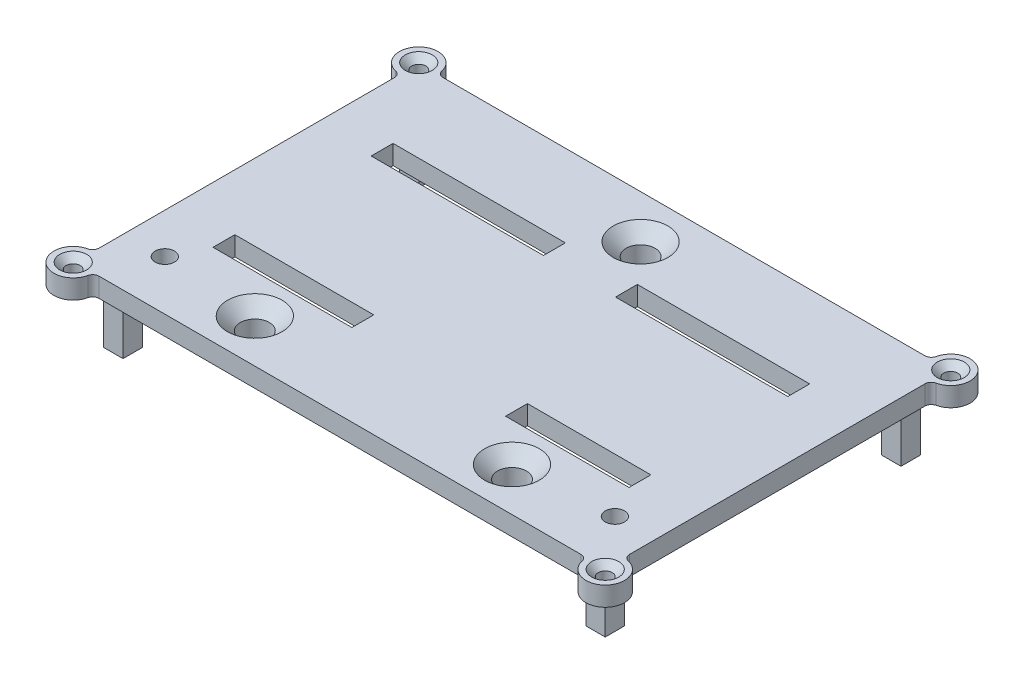
SolidWorks part; units mm, degrees
ref_plane "前视基准面" through (0, 0, 0) normal (0, 0, 1) x (1, 0, 0)
ref_plane "上视基准面" through (0, 0, 0) normal (0, 1, 0) x (1, 0, 0)
ref_plane "右视基准面" through (0, 0, 0) normal (1, 0, 0) x (0, 0, -1)
sketch "草图1" plane through (0, 0, 0) normal (0, 1, 0) x (1, 0, 0)
  line L0 (37.469, -26.75) -> (-37.469, -26.75)
  line L1 (41.25, -10.5) -> (41.25, -22.969)
  line L2 (41.25, -10.5) -> (39.25, -10.5)
  line L3 (39.25, -10.5) -> (39.25, -24.75)
  line L4 (39.25, -24.75) -> (-39.25, -24.75)
  line L5 (-39.25, -24.75) -> (-39.25, 24.75)
  line L6 (-39.25, 24.75) -> (39.25, 24.75)
  line L7 (39.25, 24.75) -> (39.25, 10.5)
  line L8 (41.25, 10.5) -> (39.25, 10.5)
  line L9 (41.25, 22.969) -> (41.25, 10.5)
  line L10 (-37.469, 26.75) -> (37.469, 26.75)
  line L11 (-41.25, -22.969) -> (-41.25, 22.969)
  circle A0 centre (41.3713, 26.8713) radius 0.85
  circle A1 centre (41.3713, -26.8713) radius 0.85
  circle A2 centre (-41.3713, -26.8713) radius 0.85
  circle A3 centre (-41.3713, 26.8713) radius 0.85
  arc A4 (38.4446, -27.5303) -> (37.469, -26.75) centre (37.469, -27.75) ccw
  arc A5 (38.4446, -27.5303) -> (42.0303, -23.9446) centre (41.3713, -26.8713) ccw
  arc A6 (41.25, -22.969) -> (42.0303, -23.9446) centre (42.25, -22.969) ccw
  arc A7 (42.0303, 23.9446) -> (41.25, 22.969) centre (42.25, 22.969) ccw
  arc A8 (42.0303, 23.9446) -> (38.4446, 27.5303) centre (41.3713, 26.8713) ccw
  arc A9 (37.469, 26.75) -> (38.4446, 27.5303) centre (37.469, 27.75) ccw
  arc A10 (-38.4446, 27.5303) -> (-37.469, 26.75) centre (-37.469, 27.75) ccw
  arc A11 (-38.4446, 27.5303) -> (-42.0303, 23.9446) centre (-41.3713, 26.8713) ccw
  arc A12 (-41.25, 22.969) -> (-42.0303, 23.9446) centre (-42.25, 22.969) ccw
  arc A13 (-42.0303, -23.9446) -> (-41.25, -22.969) centre (-42.25, -22.969) ccw
  arc A14 (-42.0303, -23.9446) -> (-38.4446, -27.5303) centre (-41.3713, -26.8713) ccw
  arc A15 (-37.469, -26.75) -> (-38.4446, -27.5303) centre (-37.469, -27.75) ccw
sketch "草图2" plane through (0, 0, 0) normal (0, 1, 0) x (1, 0, 0)
  line L0 (37.469, -26.75) -> (-37.469, -26.75) construction
  line L1 (-41.25, -22.969) -> (-41.25, 22.969) construction
  line L2 (-37.469, 26.75) -> (37.469, 26.75) construction
  line L3 (37.469, -26.75) -> (-37.469, -26.75)
  line L4 (-41.25, -22.969) -> (-41.25, 22.969)
  line L5 (-37.469, 26.75) -> (37.469, 26.75)
  line L6 (41.25, 22.969) -> (41.25, -22.969)
  line L8 (-32, 24.75) -> (-32, -24.75) construction
  line L9 (-39.25, 24.75) -> (39.25, 24.75) construction
  line L10 (39.25, -24.75) -> (-39.25, -24.75) construction
  line L11 (-39.25, -24.75) -> (-39.25, 24.75) construction
  line L12 (-39.25, 13.5) -> (39.25, 13.5) construction
  line L13 (39.25, 24.75) -> (39.25, 10.5) construction
  line L14 (-39.25, -13.5) -> (39.25, -13.5) construction
  line L15 (39.25, -10.5) -> (39.25, -24.75) construction
  line L16 (0, 24.75) -> (0, 20) construction
  line L17 (-32, 13.5) -> (-6.2, 13.5)
  line L18 (-32, 13.5) -> (-32, 11.1)
  line L19 (-32, 11.1) -> (-6.2, 11.1)
  line L20 (-6.2, 13.5) -> (-6.2, 11.1)
  line L21 (6, 13.5) -> (31.8, 13.5)
  line L22 (6, 13.5) -> (6, 11.1)
  line L23 (6, 11.1) -> (31.8, 11.1)
  line L24 (31.8, 13.5) -> (31.8, 11.1)
  line L25 (-32, -13.5) -> (-11.4, -13.5)
  line L26 (-32, -13.5) -> (-32, -11.1)
  line L27 (-32, -11.1) -> (-11.4, -11.1)
  line L28 (-11.4, -13.5) -> (-11.4, -11.1)
  line L29 (13.5, -13.5) -> (31.7, -13.5)
  line L30 (13.5, -13.5) -> (13.5, -11.1)
  line L31 (13.5, -11.1) -> (31.7, -11.1)
  line L32 (31.7, -13.5) -> (31.7, -11.1)
  line L33 (0, -24.75) -> (0, -20) construction
  line L34 (-20, -20) -> (20, -20) construction
  arc A0 (41.25, -22.969) -> (42.0303, -23.9446) centre (42.25, -22.969) ccw construction
  arc A1 (38.4446, -27.5303) -> (42.0303, -23.9446) centre (41.3713, -26.8713) ccw construction
  arc A2 (38.4446, -27.5303) -> (37.469, -26.75) centre (37.469, -27.75) ccw construction
  arc A3 (-37.469, -26.75) -> (-38.4446, -27.5303) centre (-37.469, -27.75) ccw construction
  arc A4 (-42.0303, -23.9446) -> (-38.4446, -27.5303) centre (-41.3713, -26.8713) ccw construction
  arc A5 (-42.0303, -23.9446) -> (-41.25, -22.969) centre (-42.25, -22.969) ccw construction
  arc A6 (-41.25, 22.969) -> (-42.0303, 23.9446) centre (-42.25, 22.969) ccw construction
  arc A7 (-38.4446, 27.5303) -> (-37.469, 26.75) centre (-37.469, 27.75) ccw construction
  arc A8 (-38.4446, 27.5303) -> (-42.0303, 23.9446) centre (-41.3713, 26.8713) ccw construction
  arc A9 (42.0303, 23.9446) -> (41.25, 22.969) centre (42.25, 22.969) ccw construction
  arc A10 (42.0303, 23.9446) -> (38.4446, 27.5303) centre (41.3713, 26.8713) ccw construction
  arc A11 (37.469, 26.75) -> (38.4446, 27.5303) centre (37.469, 27.75) ccw construction
  arc A12 (41.25, -22.969) -> (42.0303, -23.9446) centre (42.25, -22.969) ccw
  arc A13 (38.4446, -27.5303) -> (42.0303, -23.9446) centre (41.3713, -26.8713) ccw
  arc A14 (38.4446, -27.5303) -> (37.469, -26.75) centre (37.469, -27.75) ccw
  arc A15 (-37.469, -26.75) -> (-38.4446, -27.5303) centre (-37.469, -27.75) ccw
  arc A16 (-42.0303, -23.9446) -> (-38.4446, -27.5303) centre (-41.3713, -26.8713) ccw
  arc A17 (-42.0303, -23.9446) -> (-41.25, -22.969) centre (-42.25, -22.969) ccw
  arc A18 (-41.25, 22.969) -> (-42.0303, 23.9446) centre (-42.25, 22.969) ccw
  arc A19 (-38.4446, 27.5303) -> (-37.469, 26.75) centre (-37.469, 27.75) ccw
  arc A20 (-38.4446, 27.5303) -> (-42.0303, 23.9446) centre (-41.3713, 26.8713) ccw
  arc A21 (42.0303, 23.9446) -> (41.25, 22.969) centre (42.25, 22.969) ccw
  arc A22 (42.0303, 23.9446) -> (38.4446, 27.5303) centre (41.3713, 26.8713) ccw
  arc A23 (37.469, 26.75) -> (38.4446, 27.5303) centre (37.469, 27.75) ccw
  circle A24 centre (-41.3713, 26.8713) radius 1.1
  circle A25 centre (-41.3713, -26.8713) radius 1.1
  circle A26 centre (41.3713, -26.8713) radius 1.1
  circle A27 centre (41.3713, 26.8713) radius 1.1
  circle A28 centre (0, 20) radius 2.25
  circle A29 centre (-20, -20) radius 2.25
  circle A30 centre (20, -20) radius 2.25
  point P73 (0, -20)
  dimension "D1" = 2.2
  dimension "D18" = 4.5
  dimension "D2" = 7.25
  dimension "D3" = 11.25
  dimension "D4" = 11.25
  dimension "D5" = 25.8
  dimension "D6" = 25.8
  dimension "D7" = 2.4
  dimension "D8" = 2.4
  dimension "D9" = 12.2
  dimension "D10" = 20.6
  dimension "D11" = 18.2
  dimension "D12" = 24.9
  dimension "D13" = 2.4
  dimension "D14" = 2.4
  dimension "D15" = 4.75
  dimension "D16" = 4.75
  dimension "D17" = 19.25
extrude "凸台-拉伸1" add sketch "草图2" along normal blind 3
chamfer "倒角1" distance 1 angle 45 4 edges at (41.3713, 3, 27.9713) (41.3713, 3, -25.7713) (-41.3713, 3, -25.7713) (-41.3713, 3, 27.9713)
sketch "草图3" plane through (0, 0, 0) normal (0, 1, 0) x (1, 0, 0)
  line L0 (-32, 13.5) -> (-6.2, 11.1) construction
  line L1 (6, 13.5) -> (31.8, 11.1) construction
  line L2 (13.5, -11.1) -> (31.7, -13.5) construction
  line L3 (-32, -11.1) -> (-11.4, -13.5) construction
  line L4 (-32, 11.1) -> (-6.2, 11.1) construction
  line L5 (-32.5, 14) -> (-5.7, 14)
  line L6 (-32.5, 14) -> (-32.5, 10.6)
  line L7 (-32.5, 10.6) -> (-5.7, 10.6)
  line L8 (-5.7, 14) -> (-5.7, 10.6)
  line L9 (-32.5, 14) -> (-5.7, 10.6) construction
  line L10 (-32.5, 10.6) -> (-5.7, 14) construction
  line L11 (5.5, 14) -> (32.3, 14)
  line L12 (5.5, 14) -> (5.5, 10.6)
  line L13 (5.5, 10.6) -> (32.3, 10.6)
  line L14 (32.3, 14) -> (32.3, 10.6)
  line L15 (5.5, 14) -> (32.3, 10.6) construction
  line L16 (5.5, 10.6) -> (32.3, 14) construction
  line L17 (13, -10.6) -> (32.2, -10.6)
  line L18 (13, -10.6) -> (13, -14)
  line L19 (13, -14) -> (32.2, -14)
  line L20 (32.2, -10.6) -> (32.2, -14)
  line L21 (13, -10.6) -> (32.2, -14) construction
  line L22 (13, -14) -> (32.2, -10.6) construction
  line L23 (-32.5, -10.6) -> (-10.9, -10.6)
  line L24 (-32.5, -10.6) -> (-32.5, -14)
  line L25 (-32.5, -14) -> (-10.9, -14)
  line L26 (-10.9, -10.6) -> (-10.9, -14)
  line L27 (-32.5, -10.6) -> (-10.9, -14) construction
  line L28 (-32.5, -14) -> (-10.9, -10.6) construction
  line L29 (-32, 13.5) -> (-32, 11.1) construction
  line L30 (6, 13.5) -> (6, 11.1) construction
  line L31 (31.8, 13.5) -> (6, 13.5) construction
  line L32 (-32, -11.1) -> (-32, -13.5) construction
  line L33 (-11.4, -11.1) -> (-32, -11.1) construction
  line L34 (13.5, -11.1) -> (13.5, -13.5) construction
  line L35 (31.7, -11.1) -> (13.5, -11.1) construction
  point P16 (-19.1, 12.3)
  point P21 (18.9, 12.3)
  point P26 (22.6, -12.3)
  point P31 (-21.7, -12.3)
  dimension "D1" = 0.5
  dimension "D2" = 0.5
  dimension "D3" = 0.5
  dimension "D4" = 0.5
  dimension "D5" = 0.5
  dimension "D6" = 0.5
  dimension "D7" = 0.5
  dimension "D8" = 0.5
extrude "切除-拉伸1" cut sketch "草图3" along normal through all
chamfer "倒角2" distance 2 angle 45 3 edges at (-20, 3, 22.25) (20, 3, 22.25) (0, 3, -17.75)
sketch "草图4" plane through (0, 0, 0) normal (0, 1, 0) x (1, 0, 0)
  circle A1 centre (-20, -20) radius 2.25 construction
  circle A2 centre (20, -20) radius 2.25 construction
  circle A3 centre (0, 20) radius 2.25 construction
  circle A4 centre (-20, -20) radius 2.25
  circle A5 centre (20, -20) radius 2.25
  circle A6 centre (0, 20) radius 2.25
  circle A7 centre (-20, -20) radius 4
  circle A8 centre (20, -20) radius 4
  circle A9 centre (0, 20) radius 4
  dimension "D1" = 8
extrude "凸台-拉伸2" add sketch "草图4" against normal blind 2.2
sketch "草图5" plane through (0, 0, 0) normal (0, 1, 0) x (1, 0, 0)
  line L0 (0, 0) -> (0, 24.75) construction
  line L1 (-39.25, 24.75) -> (39.25, 24.75) construction
  line L2 (0, 0) -> (-39.25, 0) construction
  line L3 (-39.25, -24.75) -> (-39.25, 24.75) construction
  line L4 (39, 24.5) -> (39, 21.5)
  line L5 (-39, 24.5) -> (-36, 24.5)
  line L6 (-39, 24.5) -> (-39, 21.5)
  line L7 (-39, 21.5) -> (-36, 21.5)
  line L8 (-36, 24.5) -> (-36, 21.5)
  line L9 (39, 21.5) -> (36, 21.5)
  line L10 (36, 24.5) -> (36, 21.5)
  line L11 (39, 24.5) -> (36, 24.5)
  line L12 (39, -24.5) -> (36, -24.5)
  line L13 (36, -24.5) -> (36, -21.5)
  line L14 (39, -21.5) -> (36, -21.5)
  line L15 (-36, -24.5) -> (-36, -21.5)
  line L16 (-39, -21.5) -> (-36, -21.5)
  line L17 (-39, -24.5) -> (-39, -21.5)
  line L18 (-39, -24.5) -> (-36, -24.5)
  line L19 (39, -24.5) -> (39, -21.5)
  dimension "D1" = 3
  dimension "D2" = 3
  dimension "D3" = 0.25
  dimension "D4" = 0.25
extrude "凸台-拉伸3" add sketch "草图5" against normal blind 8.5
chamfer "倒角3" distance 1 angle 45 8 edges at (36, 0, 23) (37.5, 0, 21.5) (-37.5, 0, 21.5) (-36, 0, 23) (-36, 0, -23) (-37.5, 0, -21.5) (36, 0, -23) (37.5, 0, -21.5)
sketch "草图6" plane through (0, 0, 0) normal (0, 1, 0) x (1, 0, 0)
  line L0 (-39.25, -19) -> (39.25, -19) construction
  line L1 (-39.25, -24.75) -> (-39.25, 24.75) construction
  line L2 (39.25, -10.5) -> (39.25, -24.75) construction
  line L3 (39.25, -24.75) -> (-39.25, -24.75) construction
  circle A0 centre (-35, -19) radius 1.5
  circle A1 centre (35, -19) radius 1.5
  point P12 (0, 0)
  dimension "D2" = 3
  dimension "D1" = 5.75
  dimension "D3" = 4.25
  dimension "D4" = 4.25
extrude "切除-拉伸2" cut sketch "草图6" along normal through all
